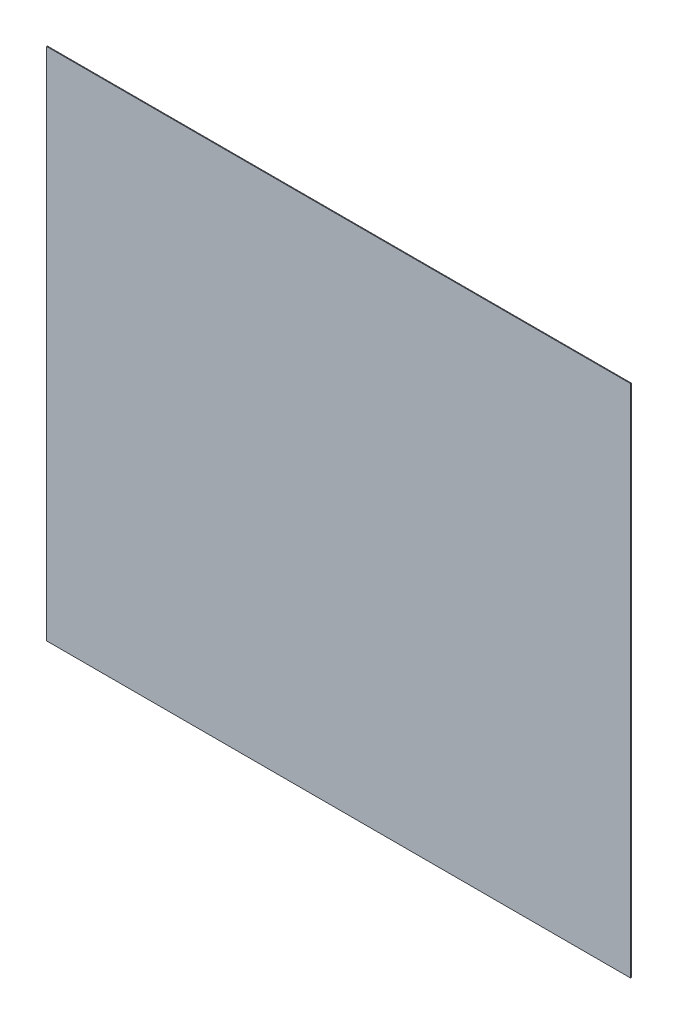
SolidWorks part; units mm, degrees
ref_plane "Front Plane" through (0, 0, 0) normal (0, 0, 1) x (1, 0, 0)
ref_plane "Top Plane" through (0, 0, 0) normal (0, 1, 0) x (1, 0, 0)
ref_plane "Right Plane" through (0, 0, 0) normal (1, 0, 0) x (0, 0, -1)
sketch "Sketch1" plane through (0, 0, 0) normal (0, 0, 1) x (1, 0, 0)
  line L1 (550, 485) -> (-550, 485)
  line L2 (550, 485) -> (550, -485)
  line L3 (550, -485) -> (-550, -485)
  line L4 (-550, 485) -> (-550, -485)
  line L5 (550, 485) -> (-550, -485) construction
  line L6 (550, -485) -> (-550, 485) construction
  point P0 (0, 0)
  dimension "D1" = 1100
  dimension "D2" = 970
extrude "Boss-Extrude1" add sketch "Sketch1" along normal blind 1.5
